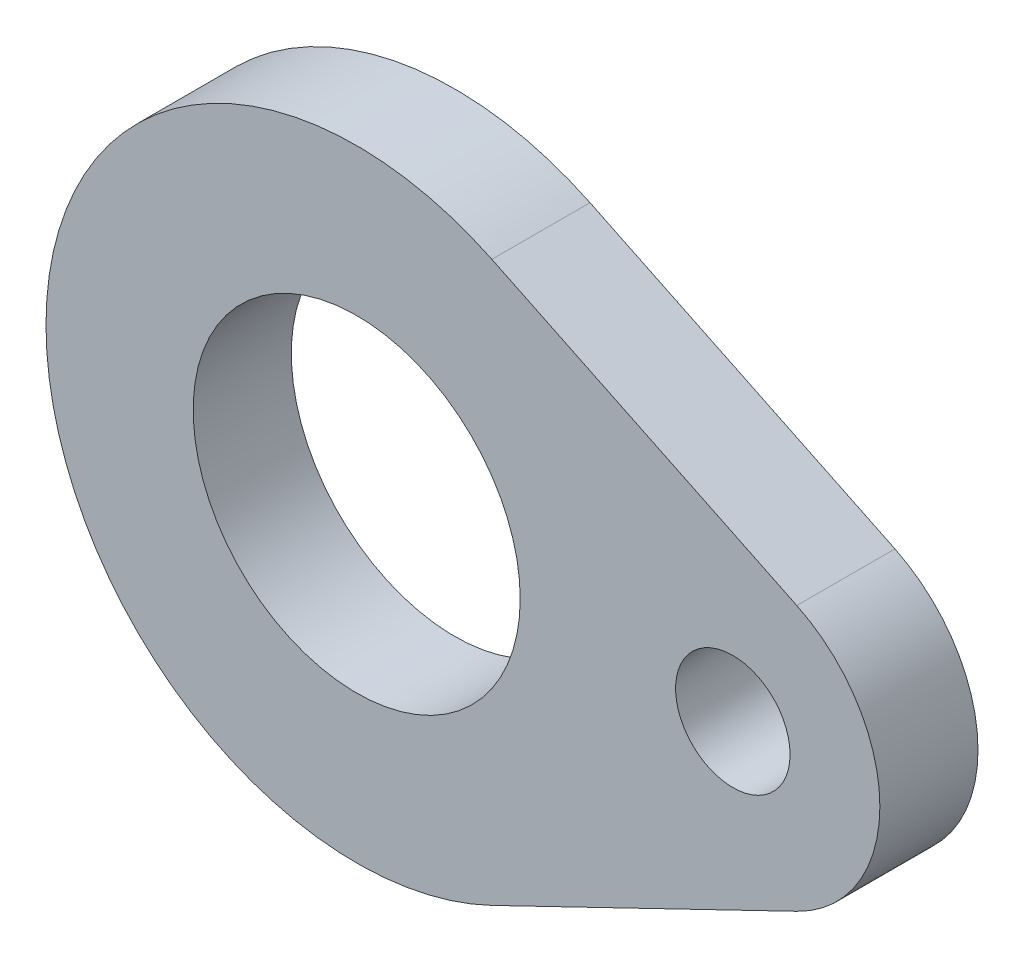
SolidWorks part; units mm, degrees
ref_plane "Front Plane" through (0, 0, 0) normal (0, 0, 1) x (1, 0, 0)
ref_plane "Top Plane" through (0, 0, 0) normal (0, 1, 0) x (1, 0, 0)
ref_plane "Right Plane" through (0, 0, 0) normal (1, 0, 0) x (0, 0, -1)
sketch "Sketch1" plane through (0, 0, 0) normal (0, 0, 1) x (1, 0, 0)
  line L0 (4.1332, 8.5537) -> (13.4564, 4.0487)
  line L1 (4.1332, -8.5537) -> (13.4564, -4.0487)
  arc A0 (4.1332, 8.5537) -> (4.1332, -8.5537) centre (0, 0) ccw
  circle A1 centre (0, 0) radius 5
  circle A3 centre (11.5, 0) radius 1.75
  arc A5 (13.4564, -4.0487) -> (13.4564, 4.0487) centre (11.5, 0) ccw
  dimension "D1" = 19
  dimension "D2" = 10
  dimension "D3" = 3.5
  dimension "D4" = 11.5
extrude "Boss-Extrude1" add sketch "Sketch1" along normal mid plane 3
